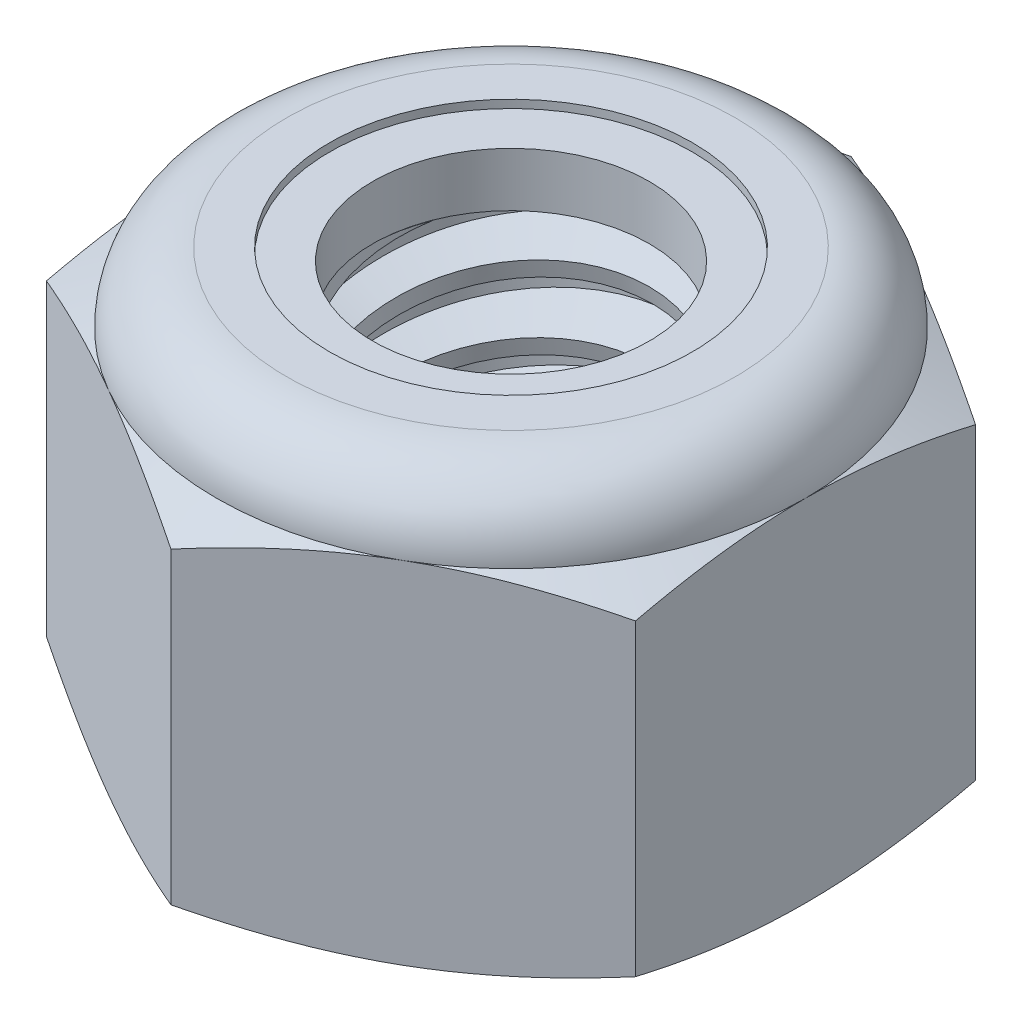
SolidWorks part; units mm, degrees
material "1023 Carbon Steel Sheet (SS)"
ref_plane "Front" through (0, 0, 0) normal (0, 0, 1) x (1, 0, 0)
ref_plane "Top" through (0, 0, 0) normal (0, 1, 0) x (1, 0, 0)
ref_plane "Right" through (0, 0, 0) normal (1, 0, 0) x (0, 0, -1)
sketch "Sketch1" plane through (0, 0, 0) normal (0, 1, 0) x (1, 0, 0)
  line L1 (0, 6.4158) -> (-5.5563, 3.2079)
  line L2 (-5.5563, 3.2079) -> (-5.5563, -3.2079)
  line L3 (-5.5563, -3.2079) -> (0, -6.4158)
  line L4 (0, -6.4158) -> (5.5562, -3.2079)
  line L5 (5.5562, -3.2079) -> (5.5562, 3.2079)
  line L6 (5.5562, 3.2079) -> (0, 6.4158)
  circle A0 centre (0, 0) radius 5.5563 construction
  dimension "Hex Flats" = 11.1125
extrude "Extrude1" add sketch "Sketch1" along normal blind 7.9375
sketch "Sketch2" plane through (0, 0, 0) normal (1, 0, 0) x (0, 0, -1)
  line L0 (-3.175, 0) -> (-3.175, 7.9375) construction
  line L1 (0, 0) -> (3.175, 0)
  line L2 (0, 0) -> (0, 7.9375)
  line L3 (0, 7.9375) -> (3.175, 7.9375)
  line L4 (3.175, 0) -> (3.175, 7.9375)
  line L5 (-3.2079, 7.9375) -> (3.2079, 7.9375) construction
  line L7 (0, -3.175) -> (0, 0) construction
  dimension "Thread Dia" = 6.35
revolve "Revolve1" add sketch "Sketch2" angle 360 about L7
sketch "Sketch3" plane through (0, 0, 0) normal (1, 0, 0) x (0, 0, -1)
  line L0 (3.175, 7.9375) -> (-3.175, 7.9375) construction
  line L1 (-3.175, 7.9375) -> (-3.175, 6.6675) construction
  line L2 (-3.175, 6.6675) -> (3.175, 7.9375) construction
  line L3 (3.175, 7.9375) -> (3.2061, 7.7818) construction
  line L4 (3.2061, 7.7818) -> (3.4241, 6.6922)
  line L5 (3.4241, 6.6922) -> (2.6722, 6.9465)
  line L6 (2.6722, 6.9465) -> (2.6099, 7.2579)
  line L7 (2.6099, 7.2579) -> (3.2061, 7.7818)
  line L8 (2.641, 7.1022) -> (3.3151, 7.237) construction
  line L9 (3.175, 7.9375) -> (3.175, 7.209) construction
  line L10 (3.175, 7.209) -> (-3.175, 5.939) construction
  line L11 (-3.175, 5.939) -> (-3.175, 6.6675) construction
  line L12 (-0.2727, 7.9375) -> (0.2727, 5.2105) construction
  line L13 (-3.175, 0) -> (-3.175, 7.9375) construction
  line L14 (0, 7.9375) -> (3.175, 7.9375) construction
  line L15 (3.175, 0) -> (3.175, 7.9375) construction
  point P13 (0, 6.574)
  dimension "D1" = 0.1588
  dimension "D2" = 0.3175
  dimension "Thread Pitch" = 1.27
  dimension "D4" = 60
  dimension "D5" = 1.27
revolve "Cut-Revolve1" cut sketch "Sketch3" angle 360 about L12
pattern_linear "LPattern1" count 6 spacing 1.27 along (0, -1, 0) count 2 spacing 1.27 along (0, 1, 0) of "Cut-Revolve1"
sketch "Sketch4" plane through (0, 0, 0) normal (1, 0, 0) x (0, 0, -1)
  line L0 (0, 7.9375) -> (3.175, 7.9375)
  line L1 (3.175, 7.9375) -> (2.6099, 7.674)
  line L2 (2.6099, 7.674) -> (2.6099, 0.2635)
  line L3 (2.6099, 0.2635) -> (3.175, 0)
  line L4 (3.175, 0) -> (0, 0)
  line L5 (0, 0) -> (0, 7.9375)
  line L6 (3.175, 0) -> (3.175, 7.9375) construction
  line L7 (0, 7.9375) -> (3.175, 7.9375) construction
  line L8 (0, 0) -> (3.175, 0) construction
  line L9 (0, 0) -> (0, 7.9375) construction
  line L10 (0, 7.9375) -> (0, 8.561) construction
  dimension "D1" = 25
revolve "Cut-Revolve2" cut sketch "Sketch4" angle 360 about L10
combine bodies "Combine1" operation type subtract main body 112 bodies to subtract 111
sketch "Sketch5" plane through (0, 0, 0) normal (1, 0, 0) x (0, 0, -1)
  line L0 (0, 0) -> (5.5563, 0)
  line L1 (5.5563, 0) -> (6.4158, 0.4008)
  line L2 (6.4158, 0.4008) -> (6.4158, 6.2138)
  line L3 (6.4158, 6.2138) -> (5.5563, 6.6146)
  line L4 (4.2333, 7.9375) -> (4.2333, 9.2075)
  line L5 (4.2333, 9.2075) -> (7.6858, 9.2075)
  line L6 (7.6858, 9.2075) -> (7.6858, -1.27)
  line L7 (7.6858, -1.27) -> (0, -1.27)
  line L8 (0, -1.27) -> (0, 0)
  line L9 (5.5563, 6.6146) -> (5.5563, 0) construction
  line L10 (0, 0) -> (3.175, 0) construction
  line L13 (6.4158, 3.3073) -> (7.6858, 3.3073) construction
  line L14 (6.4158, 7.9375) -> (6.4158, 0) construction
  line L15 (0, 0) -> (0, 9.2075) construction
  line L20 (0, 9.2075) -> (4.2333, 9.2075) construction
  line L22 (0, 7.9375) -> (3.175, 7.9375) construction
  arc A0 (5.5563, 6.6146) -> (4.2333, 7.9375) centre (4.2333, 6.6146) ccw
  dimension "D1" = 25
  dimension "D2" = 1.27
  dimension "D3" = 7.9375
  dimension "D4" = 1.3229
revolve "Cut-Revolve3" cut sketch "Sketch5" angle 360 about L15
sketch "Sketch6" plane through (0, 0, 0) normal (1, 0, 0) x (0, 0, -1)
  line L0 (0, 6.6146) -> (5.4039, 6.6146)
  line L1 (4.2333, 7.7851) -> (3.4216, 7.7851)
  line L2 (0, 9.2075) -> (0, 6.6146)
  line L3 (3.4216, 9.2075) -> (0, 9.2075)
  line L4 (0, 9.2075) -> (4.2333, 9.2075) construction
  line L5 (0, 0) -> (0, 9.2075) construction
  line L6 (0, 9.2075) -> (0, 44.323) construction
  line L7 (3.4216, 7.7851) -> (3.4216, 9.2075)
  line L8 (4.2333, 7.9375) -> (4.2333, 7.7851) construction
  line L9 (3.4216, 7.7851) -> (2.6099, 7.7851) construction
  line L10 (2.6099, 7.7851) -> (2.6099, 7.674) construction
  arc A0 (5.4039, 6.6146) -> (4.2333, 7.7851) centre (4.2333, 6.6146) ccw
  arc A1 (5.5563, 6.6146) -> (4.2333, 7.9375) centre (4.2333, 6.6146) ccw construction
  dimension "D1" = 0.1524
revolve "Cut-Revolve4" cut sketch "Sketch6" angle 360 about L6
sketch "Sketch7" plane through (0, 0, 0) normal (1, 0, 0) x (0, 0, -1)
  line L0 (2.6099, 6.6908) -> (5.325, 6.6908)
  line L1 (4.2333, 7.7089) -> (2.6099, 7.7089)
  line L2 (2.6099, 7.7089) -> (2.6099, 6.6908)
  line L3 (2.6099, 6.6908) -> (0, 6.6908) construction
  line L4 (0, 6.6908) -> (0, 7.7089) construction
  line L5 (0, 7.7089) -> (2.6099, 7.7089) construction
  line L6 (2.6099, 6.6908) -> (2.6099, 6.6146) construction
  line L7 (0, 6.6146) -> (5.4039, 6.6146) construction
  line L8 (4.2333, 7.7089) -> (4.2333, 7.7851) construction
  arc A0 (5.325, 6.6908) -> (4.2333, 7.7089) centre (4.2333, 6.6146) ccw
  arc A2 (5.4039, 6.6146) -> (4.2333, 7.7851) centre (4.2333, 6.6146) ccw construction
  dimension "D1" = 0.0762
revolve "Revolve2" add sketch "Sketch7" angle 360 about L4
equation "\"D1@Sketch3\"=\"Thread Pitch@Sketch3\"/8"
equation "\"D2@Sketch3\"=\"Thread Pitch@Sketch3\"/4"
equation "\"D5@Sketch3\"=\"Thread Pitch@Sketch3\""
equation "\"D4@LPattern1\"=\"Thread Pitch@Sketch3\""
equation "\"D3@LPattern1\"=\"Thread Pitch@Sketch3\""
equation "\"D1@LPattern1\"=\"Height@Extrude1\"/\"Thread Pitch@Sketch3\""
equation "\"D4@Sketch5\"=\"Height@Extrude1\"/6"
